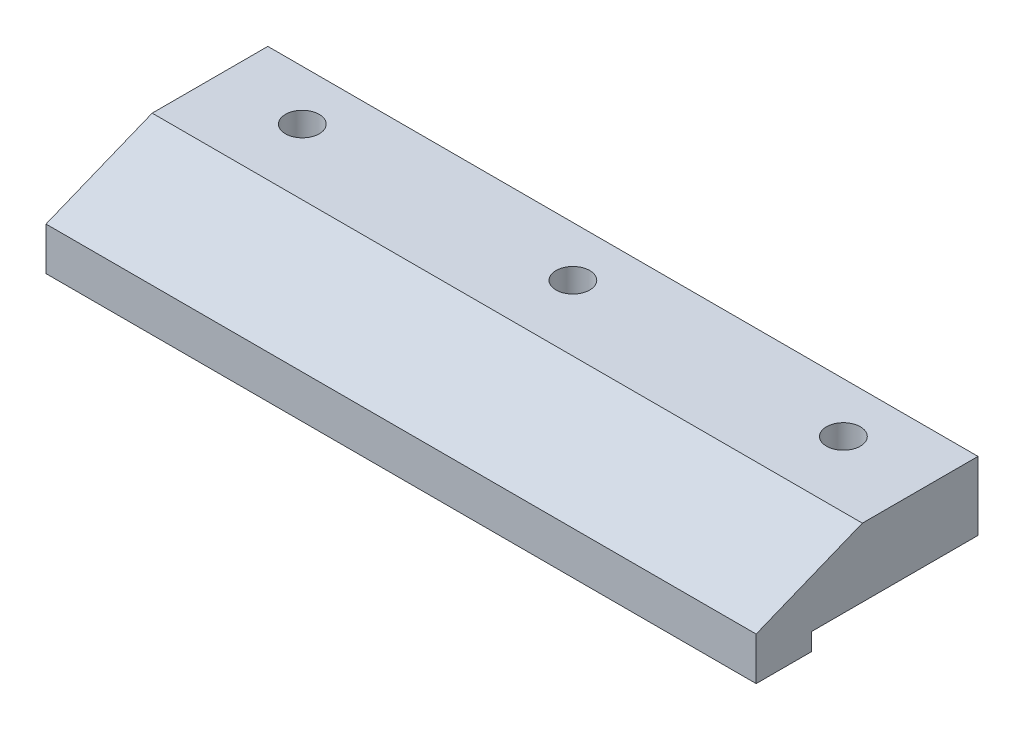
SolidWorks part; units mm, degrees
material "Aleación 1060"
ref_plane "Alzado" through (0, 0, 0) normal (0, 0, 1) x (1, 0, 0)
ref_plane "Planta" through (0, 0, 0) normal (0, 1, 0) x (1, 0, 0)
ref_plane "Vista lateral" through (0, 0, 0) normal (1, 0, 0) x (0, 0, -1)
sketch "Croquis1" plane through (0, 0, 0) normal (0, 1, 0) x (1, 0, 0)
  line L1 (52.5, -25.4) -> (-52.5, -25.4)
  line L2 (52.5, -25.4) -> (52.5, 25.4)
  line L3 (52.5, 25.4) -> (-52.5, 25.4)
  line L4 (-52.5, -25.4) -> (-52.5, 25.4)
  line L5 (52.5, -25.4) -> (-52.5, 25.4) construction
  line L6 (52.5, 25.4) -> (-52.5, -25.4) construction
  point P0 (0, 0)
  dimension "D1" = 50.8
  dimension "D2" = 105
extrude "Saliente-Extruir1" add sketch "Croquis1" along normal blind 12.7
sketch "Croquis2" plane through (52.5, 0, 0) normal (1, 0, 0) x (0, 0, -1)
  line L0 (-25.4, 0) -> (25.4, 0) construction
  line L1 (-25.4, 12.7) -> (-25.4, 0) construction
  line L3 (25.4, 12.7) -> (7.4, 12.7)
  line L4 (-25.4, 6.35) -> (-9.701, 12.7)
  line L5 (-25.4, 12.7) -> (25.4, 12.7) construction
  line L6 (-9.701, 12.7) -> (-25.4, 12.7)
  line L7 (-25.4, 12.7) -> (-25.4, 6.35)
  line L8 (25.4, 12.7) -> (25.4, 0)
  line L9 (25.4, 0) -> (7.4, 0)
  line L10 (7.4, 12.7) -> (7.4, 0)
  line L12 (7.4, 0) -> (-17.2502, 0)
  line L13 (7.4, 0) -> (7.4, 2.5754)
  line L14 (7.4, 2.5754) -> (-17.2502, 2.5754)
  line L15 (-17.2502, 0) -> (-17.2502, 2.5754)
  line M1 (-25.4, 0) -> (25.4, 0)
  line M2 (25.4, 0) -> (25.4, 12.7)
  line M3 (25.4, 12.7) -> (-25.4, 12.7)
  line M4 (-25.4, 12.7) -> (-25.4, 0)
  dimension "D1" = 18
extrude "Cortar-Extruir1" cut sketch "Croquis2" against normal through all contours L4 M4 M3 | L15 L10 L14 M1 | L10 M3 M1 M2
sketch "Croquis3" plane through (0, 12.7, 0) normal (0, 1, 0) x (1, 0, 0)
  line L0 (-52.5, 0) -> (52.5, 0) construction
  line L1 (52.5, -9.701) -> (52.5, 7.4) construction
  circle A0 centre (0, 0) radius 2.5
  circle A1 centre (-40, 0) radius 2.5
  circle A2 centre (40, 0) radius 2.5
  point P6 (0, 0)
  dimension "D1" = 5
  dimension "D2" = 5
  dimension "D3" = 5
  dimension "D4" = 80
  dimension "D5" = 40
extrude "Cortar-Extruir2" cut sketch "Croquis3" against normal through all
